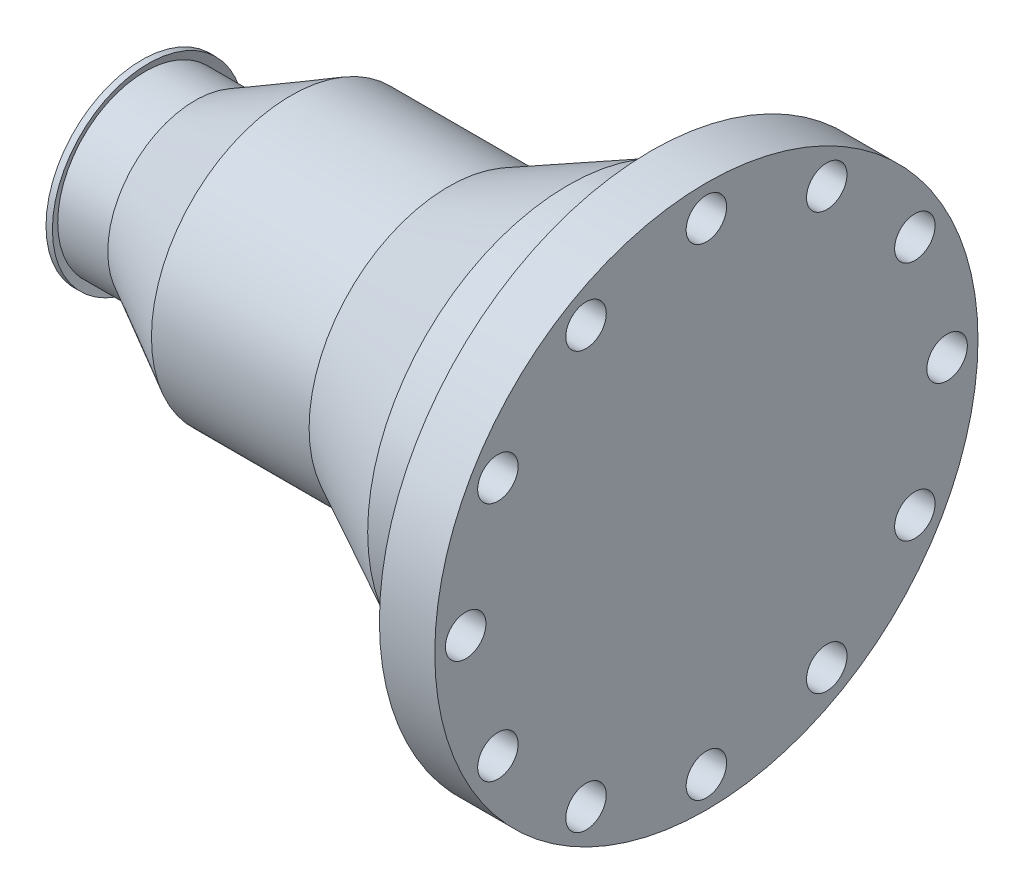
SolidWorks part; units mm, degrees
ref_plane "Спереди" through (0, 0, 0) normal (0, 0, 1) x (1, 0, 0)
ref_plane "Сверху" through (0, 0, 0) normal (0, 1, 0) x (1, 0, 0)
ref_plane "Справа" through (0, 0, 0) normal (1, 0, 0) x (0, 0, -1)
sketch "Эскиз1" plane through (0, 0, 0) normal (0, 0, 1) x (1, 0, 0)
  line L0 (0, 0) -> (265, 0)
  line L1 (0, 0) -> (0, 45)
  line L2 (0, 45) -> (3, 45)
  line L3 (3, 45) -> (1.5, 41)
  line L4 (1.5, 41) -> (25, 41)
  line L5 (25, 41) -> (70, 65.5)
  line L6 (70, 65.5) -> (144, 65.5)
  line L7 (144, 65.5) -> (200, 94)
  line L8 (200, 94) -> (220, 94)
  line L9 (220, 94) -> (220, 95)
  line L10 (220, 95) -> (239, 95)
  line L11 (239, 95) -> (239, 100)
  line L12 (239, 100) -> (239, 127.5)
  line L13 (239, 127.5) -> (265, 127.5)
  line L14 (265, 127.5) -> (265, 0)
revolve "Повернуть1" add sketch "Эскиз1" angle 360 about L0
sketch "Эскиз2" plane through (0, 0, 0) normal (0, 0, 1) x (1, 0, 0)
  line L0 (0, 0) -> (257, 0)
  line L1 (0, 0) -> (0, 31)
  line L2 (0, 45) -> (0, -45) construction
  line L3 (0, 31) -> (42, 31)
  line L4 (42, 31) -> (70, 38.5026)
  line L5 (70, 65.5) -> (70, -65.5) construction
  line L6 (90, 52.5) -> (142, 52.5)
  line L7 (143.5, 52.5) -> (146.6699, 52.5)
  line L8 (147.6699, 55) -> (203.5, 55)
  line L9 (203.5, 55) -> (203.5, 47)
  line L10 (203.5, 47) -> (226, 47)
  line L11 (226, 47) -> (239, 34)
  line L12 (239, 95) -> (239, -95) construction
  line L13 (239, 34) -> (257, 34)
  line L14 (257, 34) -> (257, 0)
  arc A0 (70, 38.5026) -> (90, 52.5) centre (107.8022, 5.7765) cw
  arc A1 (142, 52.5) -> (143.5, 52.5) centre (142.75, 49.8032) cw
  arc A2 (146.6699, 52.5) -> (147.6699, 55) centre (147.5934, 53.5806) cw
revolve "Вырез-Повернуть1" cut sketch "Эскиз2" angle 360 about L0
sketch "Эскиз3" plane through (0, 0, 0) normal (1, 0, 0) x (0, 0, -1)
  circle A0 centre (0, 113) radius 9.5
extrude "Вырез-Вытянуть1" cut sketch "Эскиз3" along normal through all
sketch "Эскиз4" plane through (0, 0, 0) normal (1, 0, 0) x (0, 0, -1)
  circle A0 centre (-56.5, 97.8609) radius 9.5
extrude "Вырез-Вытянуть2" cut sketch "Эскиз4" along normal through all
sketch "Эскиз5" plane through (0, 0, 0) normal (1, 0, 0) x (0, 0, -1)
  circle A0 centre (-97.8609, 56.5) radius 9.5
extrude "Вырез-Вытянуть3" cut sketch "Эскиз5" along normal through all
sketch "Эскиз6" plane through (0, 0, 0) normal (1, 0, 0) x (0, 0, -1)
  circle A0 centre (-113, 0) radius 9.5
extrude "Вырез-Вытянуть4" cut sketch "Эскиз6" along normal through all
sketch "Эскиз7" plane through (0, 0, 0) normal (1, 0, 0) x (0, 0, -1)
  circle A0 centre (-97.8609, -56.5) radius 9.5
extrude "Вырез-Вытянуть5" cut sketch "Эскиз7" along normal through all
sketch "Эскиз8" plane through (0, 0, 0) normal (1, 0, 0) x (0, 0, -1)
  circle A0 centre (-56.5, -97.8609) radius 9.5
extrude "Вырез-Вытянуть6" cut sketch "Эскиз8" along normal through all
sketch "Эскиз9" plane through (0, 0, 0) normal (1, 0, 0) x (0, 0, -1)
  circle A0 centre (0, -113) radius 9.5
extrude "Вырез-Вытянуть7" cut sketch "Эскиз9" along normal through all
sketch "Эскиз10" plane through (0, 0, 0) normal (1, 0, 0) x (0, 0, -1)
  circle A0 centre (56.5, -97.8609) radius 9.5
extrude "Вырез-Вытянуть8" cut sketch "Эскиз10" along normal through all
sketch "Эскиз11" plane through (0, 0, 0) normal (1, 0, 0) x (0, 0, -1)
  circle A0 centre (97.8609, -56.5) radius 9.5
extrude "Вырез-Вытянуть9" cut sketch "Эскиз11" along normal through all
sketch "Эскиз12" plane through (0, 0, 0) normal (1, 0, 0) x (0, 0, -1)
  circle A0 centre (113, 0) radius 9.5
extrude "Вырез-Вытянуть10" cut sketch "Эскиз12" along normal through all
sketch "Эскиз13" plane through (0, 0, 0) normal (1, 0, 0) x (0, 0, -1)
  circle A0 centre (97.8609, 56.5) radius 9.5
extrude "Вырез-Вытянуть11" cut sketch "Эскиз13" along normal through all
sketch "Эскиз14" plane through (0, 0, 0) normal (1, 0, 0) x (0, 0, -1)
  circle A0 centre (56.5, 97.8609) radius 9.5
extrude "Вырез-Вытянуть12" cut sketch "Эскиз14" along normal through all
